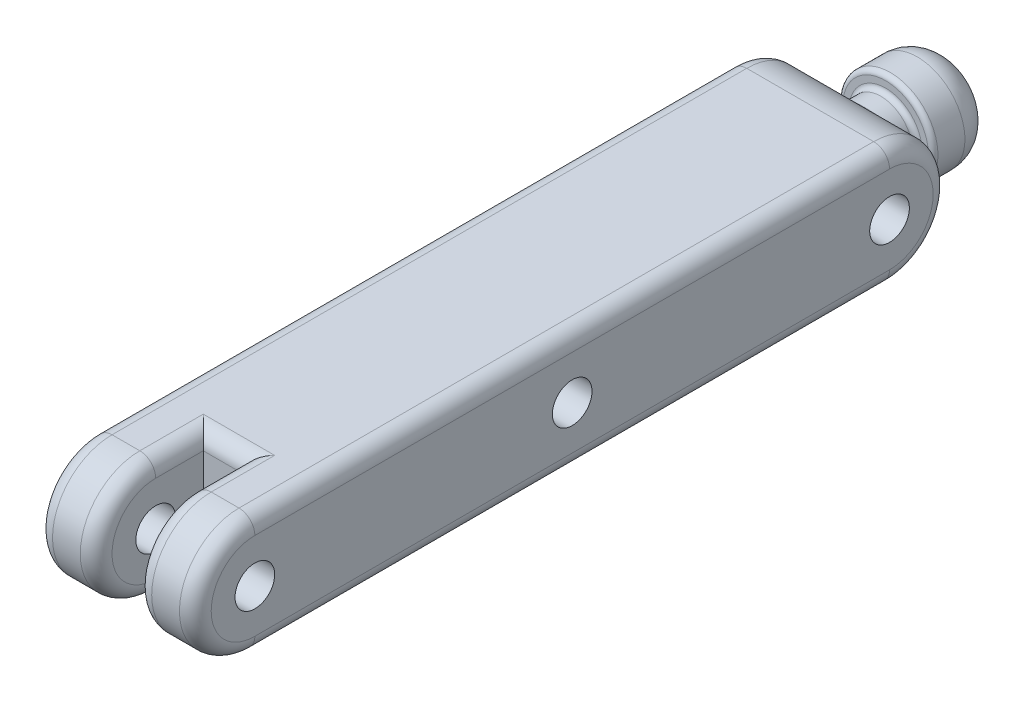
SolidWorks part; units mm, degrees
material "ABS"
ref_plane "Front" through (0, 0, 0) normal (0, 0, 1) x (1, 0, 0)
ref_plane "Top" through (0, 0, 0) normal (0, 1, 0) x (1, 0, 0)
ref_plane "Right" through (0, 0, 0) normal (1, 0, 0) x (0, 0, -1)
sketch "Sketch1" plane through (0, 0, 0) normal (1, 0, 0) x (0, 0, -1)
  line L0 (-25.4, 4.7625) -> (25.4, 4.7625)
  line L1 (25.4, -4.7625) -> (-25.4, -4.7625)
  circle A0 centre (0, 0) radius 1.5875
  circle A1 centre (25.4, 0) radius 1.5875
  arc A2 (25.4, 4.7625) -> (25.4, -4.7625) centre (25.4, 0) cw
  arc A3 (-25.4, 4.7625) -> (-25.4, -4.7625) centre (-25.4, 0) ccw
  circle A4 centre (-25.4, 0) radius 1.5875
  dimension "D1" = 3.175
  dimension "D2" = 25.4
  dimension "D3" = 9.525
  dimension "D4" = 25.4
extrude "Boss-Extrude1" add sketch "Sketch1" along normal blind 12.7
sketch3d "3DSketch1"
  line L0 (6.35, 4.7625, 25.4) -> (6.35, 4.7625, 21.59)
  line L1 (12.7, 4.7625, 25.4) -> (0, 4.7625, 25.4) construction
  line L2 (12.7, -4.7625, 25.4) -> (0, -4.7625, 25.4) construction
  line L3 (6.35, -4.7625, 21.59) -> (6.35, -4.7625, 25.4)
  line L4 (6.35, 4.7625, 21.59) -> (6.35, -4.7625, 21.59)
  arc A0 (6.35, 4.7625, 25.4) -> (6.35, -4.7625, 25.4) centre (6.35, 0, 25.4) ccw
  point P5 (11.1125, 0, 25.4)
  dimension "D1" = 3.81
extrude "Cut-Extrude1" cut sketch "3DSketch1" along direction (1, 0, 0) on the side against the normal mid plane 3.175
fillet "Fillet1" radius 1.27 15 edges at (12.7, 0, -30.1625) (12.7, -4.7625, 0) (12.7, 0, 30.1625) (0, 0, -30.1625) (0, -4.7625, 0) (0, 0, 30.1625) (12.7, 4.7625, 0) (0, 4.7625, 0)
ref_plane "Plane1" through (0, 0, -30.1625) normal (0, 0, -1) x (-1, 0, 0)
sketch "Sketch2" plane through (0, 0, -30.1625) normal (0, 0, -1) x (-1, 0, 0)
  line L0 (-11.43, 4.7625) -> (-11.43, -4.7625) construction
  line L1 (-11.43, 4.7625) -> (-1.27, 4.7625) construction
  circle A0 centre (-6.35, 0) radius 2.54
  point P4 (-11.43, 0)
  point P7 (-6.35, 4.7625)
  dimension "D1" = 5.08
extrude "Boss-Extrude2" add sketch "Sketch2" against normal up to body and the other way blind 1.27 separate body
sketch "Sketch6" plane through (0, 0, -31.4325) normal (0, 0, -1) x (-1, 0, 0)
  circle A0 centre (-6.35, 0) radius 3.81
  dimension "D1" = 7.62
extrude "Boss-Extrude3" add sketch "Sketch6" along normal blind 5.08
fillet "Fillet2" radius 2.54 1 edges at (2.54, 0, -36.5125)
fillet "Fillet3" radius 0.381 3 edges at (2.54, 0, -31.4325) (3.81, 0, -31.4325) (3.8191, 0.2148, -30.1577)
